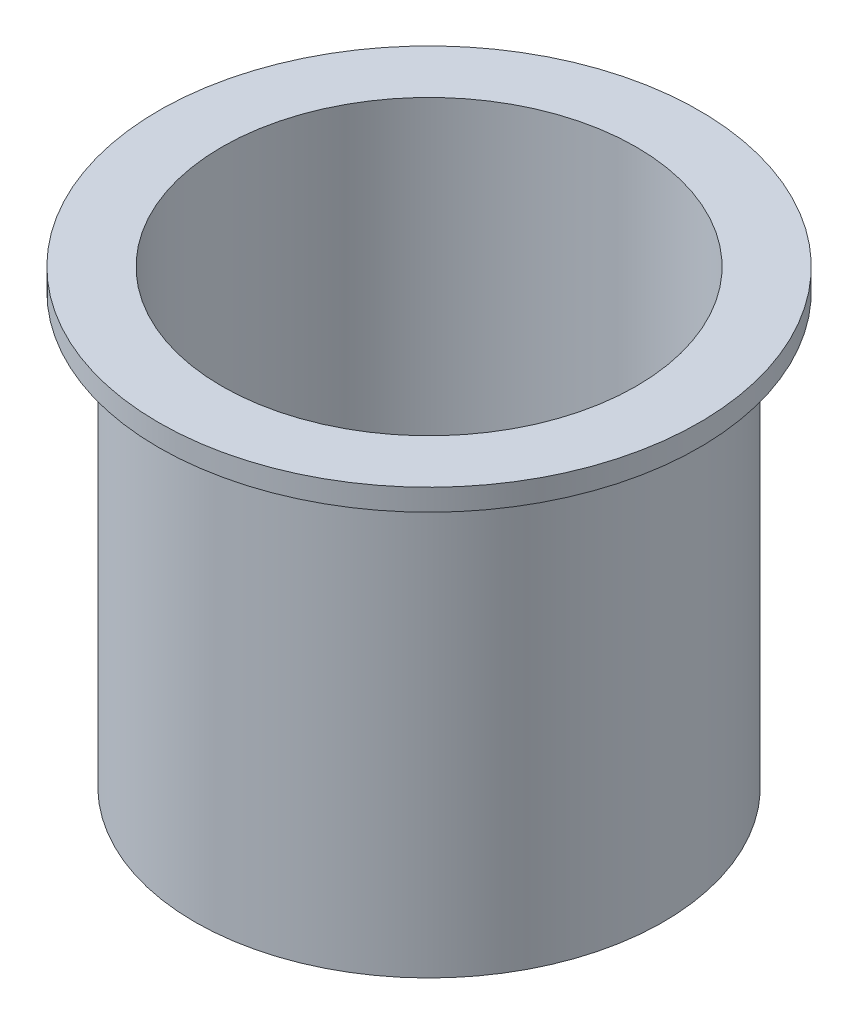
SolidWorks part; units mm, degrees
ref_plane "Front Plane" through (0, 0, 0) normal (0, 0, 1) x (1, 0, 0)
ref_plane "Top Plane" through (0, 0, 0) normal (0, 1, 0) x (1, 0, 0)
ref_plane "Right Plane" through (0, 0, 0) normal (1, 0, 0) x (0, 0, -1)
sketch "Pot Base Sketch" plane through (0, 0, 0) normal (0, 1, 0) x (1, 0, 0)
  circle A0 centre (0, 0) radius 130
  dimension "D1" = 260
extrude "Pot Base" add sketch "Pot Base Sketch" along normal blind 15
sketch "Pot Wall Sketch" plane through (0, 0, 0) normal (0, 1, 0) x (1, 0, 0)
  circle A0 centre (0, 0) radius 130
  circle A1 centre (0, 0) radius 115
  dimension "D1" = 260
  dimension "D2" = 230
extrude "Pot Wall" add sketch "Pot Wall Sketch" along normal blind 250
sketch "Pot Rim Sketch" plane through (0, 0, 0) normal (0, 1, 0) x (1, 0, 0)
  circle A0 centre (0, 0) radius 150
  circle A1 centre (0, 0) radius 115
  dimension "D1" = 300
  dimension "D2" = 230
extrude "Pot Rim" add sketch "Pot Rim Sketch" along normal blind 12 from offset 238
